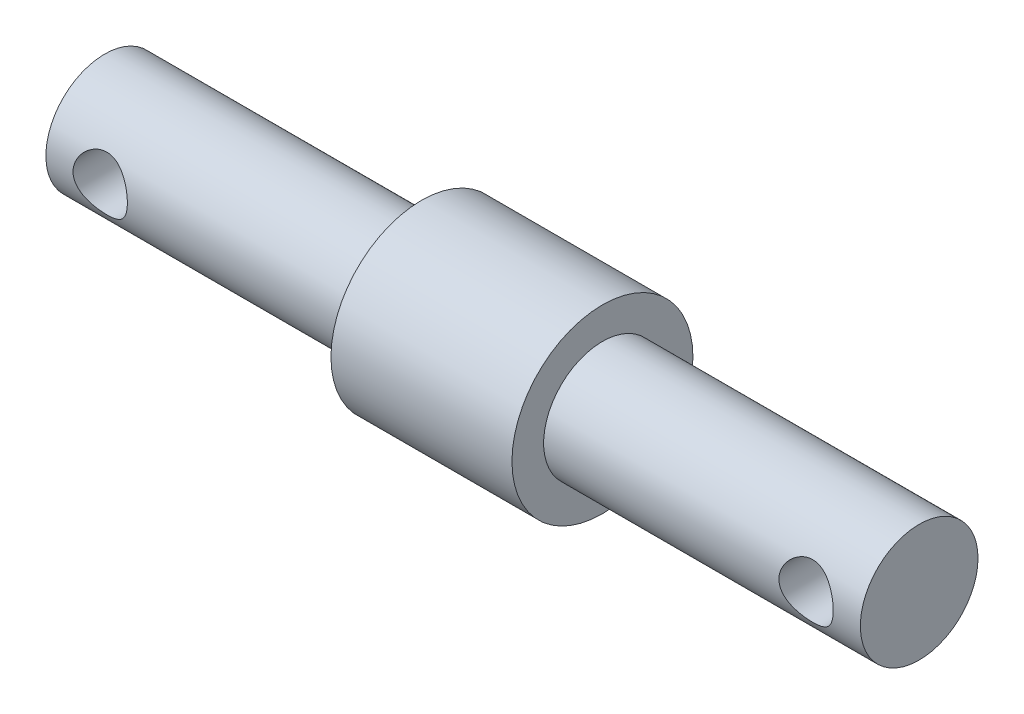
SolidWorks part; units mm, degrees
material "Plain Carbon Steel"
ref_plane "Front Plane" through (0, 0, 0) normal (0, 0, 1) x (1, 0, 0)
ref_plane "Top Plane" through (0, 0, 0) normal (0, 1, 0) x (1, 0, 0)
ref_plane "Right Plane" through (0, 0, 0) normal (1, 0, 0) x (0, 0, -1)
sketch "Sketch1" plane through (0, 0, 0) normal (1, 0, 0) x (0, 0, -1)
  circle A0 centre (0, 0) radius 3.25
  dimension "D1" = 6.5
extrude "Boss-Extrude1" add sketch "Sketch1" along normal mid plane 45
sketch "Sketch2" plane through (0, 0, 0) normal (0, 0, 1) x (1, 0, 0)
  line L0 (2.75, 0) -> (-2.75, 0) construction
  line L1 (-22.5, 3.25) -> (-22.5, -3.25) construction
  line L2 (22.5, -3.25) -> (22.5, 3.25) construction
  circle A0 centre (-19.5, 0) radius 1.5
  circle A1 centre (19.5, 0) radius 1.5
  dimension "D1" = 3
  dimension "D2" = 3
  dimension "D3" = 3
extrude "Cut-Extrude1" cut sketch "Sketch2" against normal mid plane 30
sketch "Sketch3" plane through (0, 0, 0) normal (1, 0, 0) x (0, 0, -1)
  circle A0 centre (0, 0) radius 5
  dimension "D1" = 10
extrude "Boss-Extrude2" add sketch "Sketch3" along normal mid plane 10
